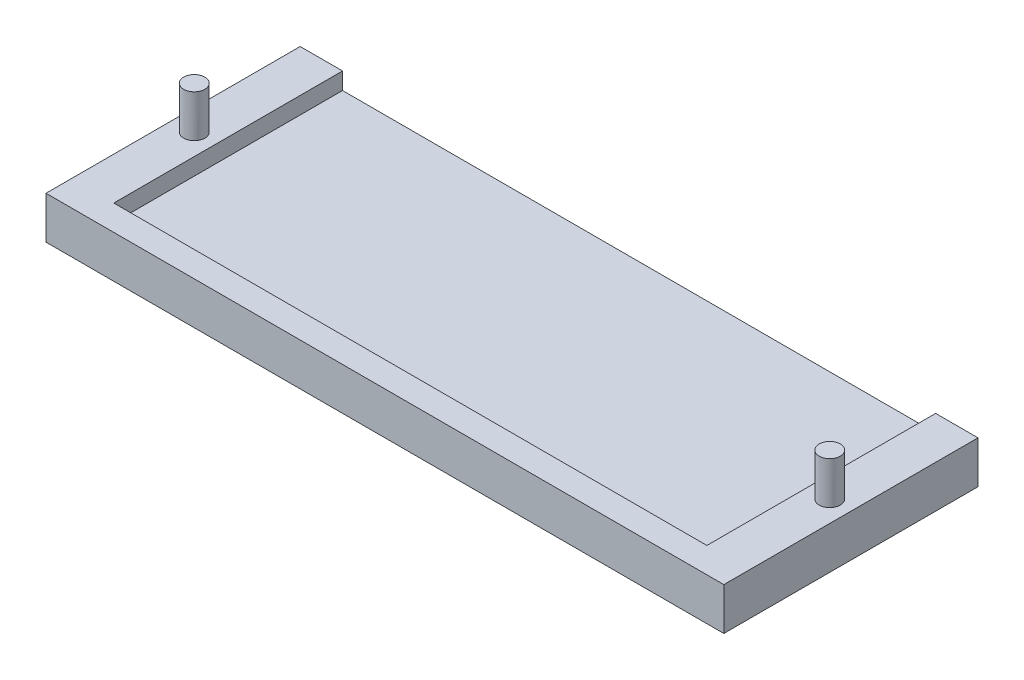
SolidWorks part; units mm, degrees
ref_plane "Front Plane" through (0, 0, 0) normal (0, 0, 1) x (1, 0, 0)
ref_plane "Top Plane" through (0, 0, 0) normal (0, 1, 0) x (1, 0, 0)
ref_plane "Right Plane" through (0, 0, 0) normal (1, 0, 0) x (0, 0, -1)
sketch "Sketch1" plane through (0, 0, 0) normal (0, 1, 0) x (1, 0, 0)
  line L1 (-45.72, 30.0703) -> (157.48, 30.0703)
  line L2 (-45.72, 30.0703) -> (-45.72, -46.1297)
  line L3 (-45.72, -46.1297) -> (157.48, -46.1297)
  line L4 (157.48, 30.0703) -> (157.48, -46.1297)
  dimension "D1" = 76.2
  dimension "D2" = 203.2
extrude "Boss-Extrude1" add sketch "Sketch1" along normal blind 12.7 contours L2 L3 L4 L1
sketch "Sketch2" plane through (0, 12.7, 0) normal (0, 1, 0) x (1, 0, 0)
  line L0 (157.48, 30.0703) -> (157.48, -46.1297) construction
  line L1 (-33.02, 30.0703) -> (144.78, 30.0703)
  line L2 (-33.02, 30.0703) -> (-33.02, -38.5097)
  line L3 (-33.02, -38.5097) -> (144.78, -38.5097)
  line L4 (144.78, 30.0703) -> (144.78, -38.5097)
  line L5 (-33.02, 30.0703) -> (144.78, -38.5097) construction
  line L6 (-33.02, -38.5097) -> (144.78, 30.0703) construction
  line L7 (-45.72, -46.1297) -> (157.48, -46.1297) construction
  point P0 (55.88, -4.2197)
  dimension "D1" = 177.8
  dimension "D2" = 68.58
  dimension "D3" = 12.7
  dimension "D4" = 7.62
extrude "Cut-Extrude1" cut sketch "Sketch2" against normal blind 5.08
sketch "Sketch3" plane through (0, 12.7, 0) normal (0, 1, 0) x (1, 0, 0)
  line L0 (157.48, 30.0703) -> (157.48, -46.1297) construction
  line L1 (144.78, 30.0703) -> (157.48, 30.0703) construction
  circle A0 centre (151.13, -8.0297) radius 3.175
  dimension "D2" = 6.35
  dimension "D1" = 6.35
  dimension "D3" = 38.1
extrude "Boss-Extrude3" add sketch "Sketch3" along normal blind 12.7
sketch "Sketch4" plane through (0, 12.7, 0) normal (0, 1, 0) x (1, 0, 0)
  line L0 (-45.72, 30.0703) -> (-45.72, -46.1297) construction
  line L1 (-45.72, -46.1297) -> (157.48, -46.1297) construction
  circle A0 centre (-39.37, -8.0297) radius 3.175
  dimension "D1" = 6.35
  dimension "D2" = 6.35
  dimension "D3" = 38.1
extrude "Boss-Extrude4" add sketch "Sketch4" along normal blind 12.7
sketch "Sketch5" plane through (0, 0, 0) normal (0, -1, 0) x (1, 0, 0)
  text T0 "FoodLocker" font "Biondi" height in points 72
extrude "Boss-Extrude6" add sketch "Sketch5" along normal blind 1.27
